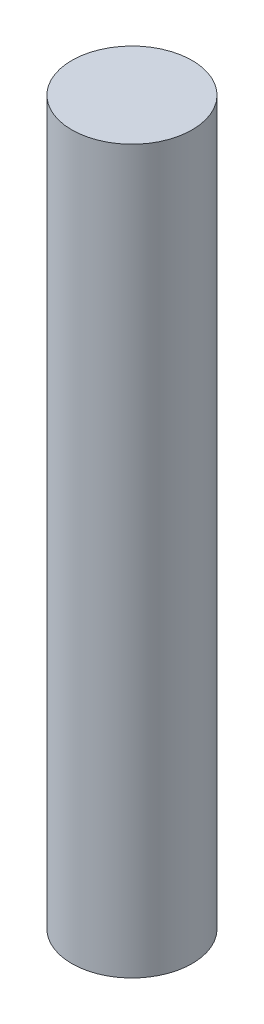
SolidWorks part; units mm, degrees
ref_plane "前视基准面" through (0, 0, 0) normal (0, 0, 1) x (1, 0, 0)
ref_plane "上视基准面" through (0, 0, 0) normal (0, 1, 0) x (1, 0, 0)
ref_plane "右视基准面" through (0, 0, 0) normal (1, 0, 0) x (0, 0, -1)
other "Configuration Table"
sketch "草图1" plane through (0, 0, 0) normal (0, 1, 0) x (1, 0, 0)
  circle A0 centre (0, 0) radius 2.5
extrude "凸台-拉伸1" add sketch "草图1" along normal blind 30
